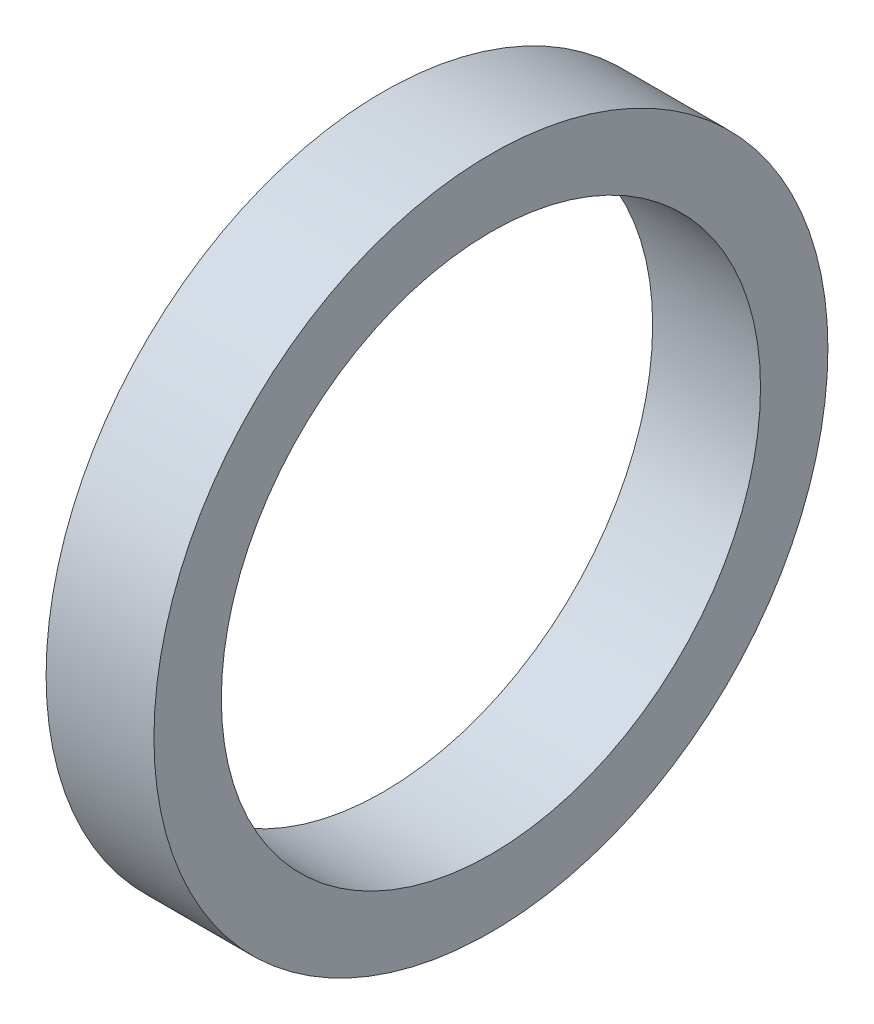
SolidWorks part; units mm, degrees
ref_plane "前视基准面" through (0, 0, 0) normal (0, 0, 1) x (1, 0, 0)
ref_plane "上视基准面" through (0, 0, 0) normal (0, 1, 0) x (1, 0, 0)
ref_plane "右视基准面" through (0, 0, 0) normal (1, 0, 0) x (0, 0, -1)
sketch "草图1" plane through (0, 0, 0) normal (1, 0, 0) x (0, 0, -1)
  circle A0 centre (0, 0) radius 20
  circle A1 centre (0, 0) radius 25
  dimension "D1" = 50
  dimension "D2" = 40
extrude "凸台-拉伸1" add sketch "草图1" along normal blind 8
